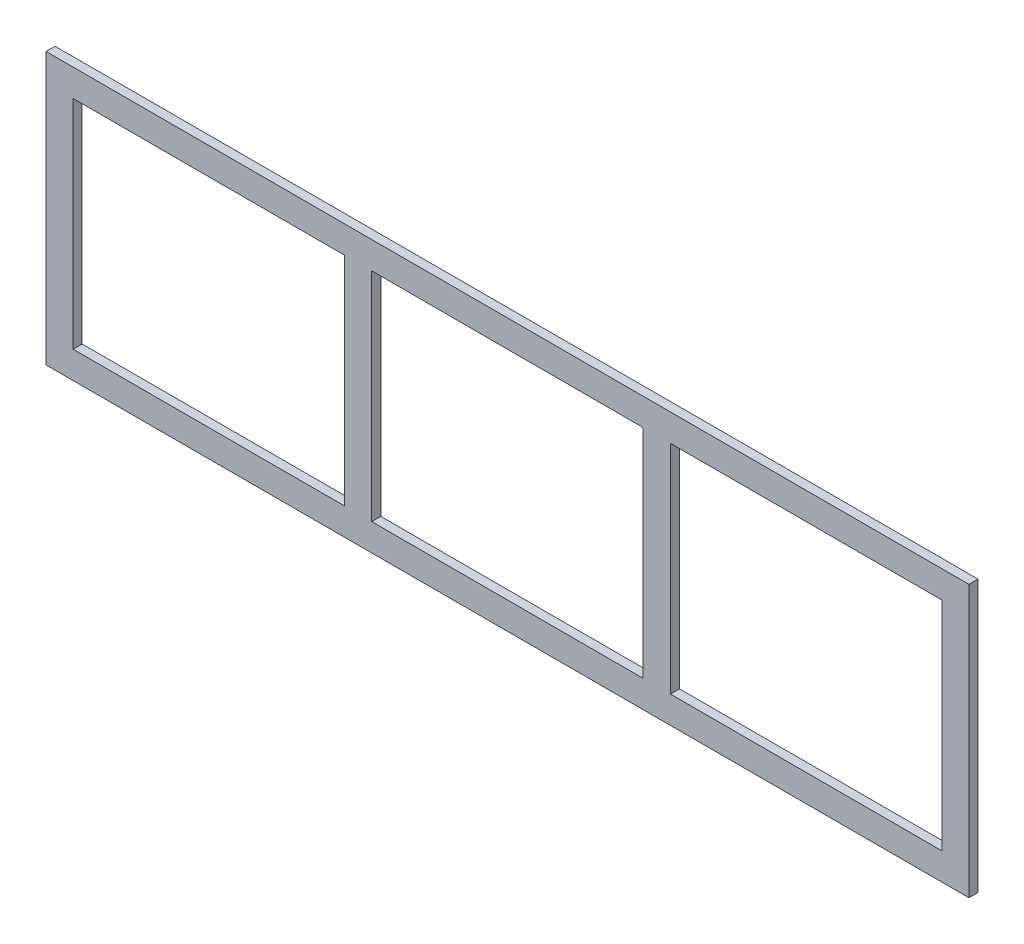
SolidWorks part; units mm, degrees
ref_plane "Front Plane" through (0, 0, 0) normal (0, 0, 1) x (1, 0, 0)
ref_plane "Top Plane" through (0, 0, 0) normal (0, 1, 0) x (1, 0, 0)
ref_plane "Right Plane" through (0, 0, 0) normal (1, 0, 0) x (0, 0, -1)
sketch "Sketch1" plane through (0, 0, 0) normal (0, 0, 1) x (1, 0, 0)
  line L0 (-900, 600) -> (-2400, 600)
  line L1 (2550, -750) -> (-2550, -750)
  line L2 (2550, -750) -> (2550, 750)
  line L3 (2550, 750) -> (-2550, 750)
  line L4 (-2550, -750) -> (-2550, 750)
  line L5 (2550, -750) -> (-2550, 750) construction
  line L6 (2550, 750) -> (-2550, -750) construction
  line L7 (2400, -600) -> (900, -600)
  line L8 (2400, -600) -> (2400, 600)
  line L9 (2400, 600) -> (900, 600)
  line L10 (-2400, -600) -> (-2400, 600)
  line L11 (2400, -600) -> (-2400, 600) construction
  line L12 (2400, 600) -> (-2400, -600) construction
  line L13 (-2400, 600) -> (-900, 600)
  line L14 (-2400, 600) -> (-2400, -600)
  line L15 (-2400, -600) -> (-900, -600)
  line L16 (-900, 600) -> (-900, -600)
  line L17 (-2400, 600) -> (-900, -600) construction
  line L18 (-2400, -600) -> (-900, 600) construction
  line L20 (-900, 600) -> (-900, -600)
  line L22 (-750, 600) -> (-750, -600)
  line L23 (-900, 600) -> (-750, -600) construction
  line L24 (-900, -600) -> (-750, 600) construction
  line L25 (-750, 600) -> (750, 600)
  line L26 (-750, 600) -> (-750, -600)
  line L27 (-750, -600) -> (750, -600)
  line L28 (750, 600) -> (750, -600)
  line L29 (-750, 600) -> (750, -600) construction
  line L30 (-750, -600) -> (750, 600) construction
  line L32 (750, 600) -> (750, -600)
  line L34 (900, 600) -> (900, -600)
  line L35 (750, 600) -> (900, -600) construction
  line L36 (750, -600) -> (900, 600) construction
  line L37 (-900, -600) -> (-2400, -600)
  line L38 (750, -600) -> (-750, -600)
  line L39 (750, 600) -> (-750, 600)
  point P0 (0, 0)
  point P6 (0, 0)
  point P13 (-1650, 0)
  point P16 (-825, 0)
  point P19 (0, 0)
  point P22 (825, 0)
  dimension "D1" = 5100
  dimension "D2" = 1500
  dimension "D3" = 150
  dimension "D4" = 150
  dimension "D5" = 1500
  dimension "D6" = 150
  dimension "D7" = 1500
  dimension "D8" = 150
  dimension "D9" = 1500
extrude "Boss-Extrude1" add sketch "Sketch1" along normal blind 50 contours L4 L1 L2 L3 L34 L9 L8 L7 L0 L16 L15 L10 L25 L28 L27 L22
